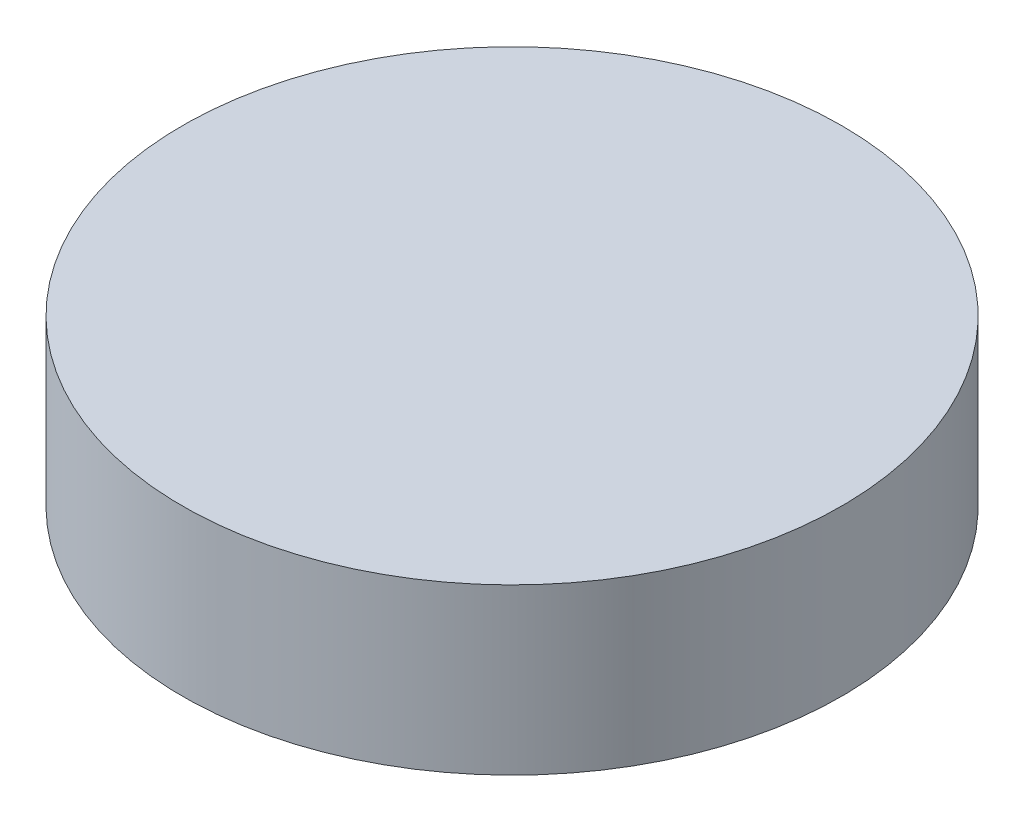
SolidWorks part; units mm, degrees
ref_plane "Front Plane" through (0, 0, 0) normal (0, 0, 1) x (1, 0, 0)
ref_plane "Top Plane" through (0, 0, 0) normal (0, 1, 0) x (1, 0, 0)
ref_plane "Right Plane" through (0, 0, 0) normal (1, 0, 0) x (0, 0, -1)
sketch "Sketch1" plane through (0, 0, 0) normal (0, 1, 0) x (1, 0, 0)
  circle A0 centre (0, 0) radius 38.1
  dimension "D1" = 76.2
extrude "Boss-Extrude1" add sketch "Sketch1" along normal blind 19.05
